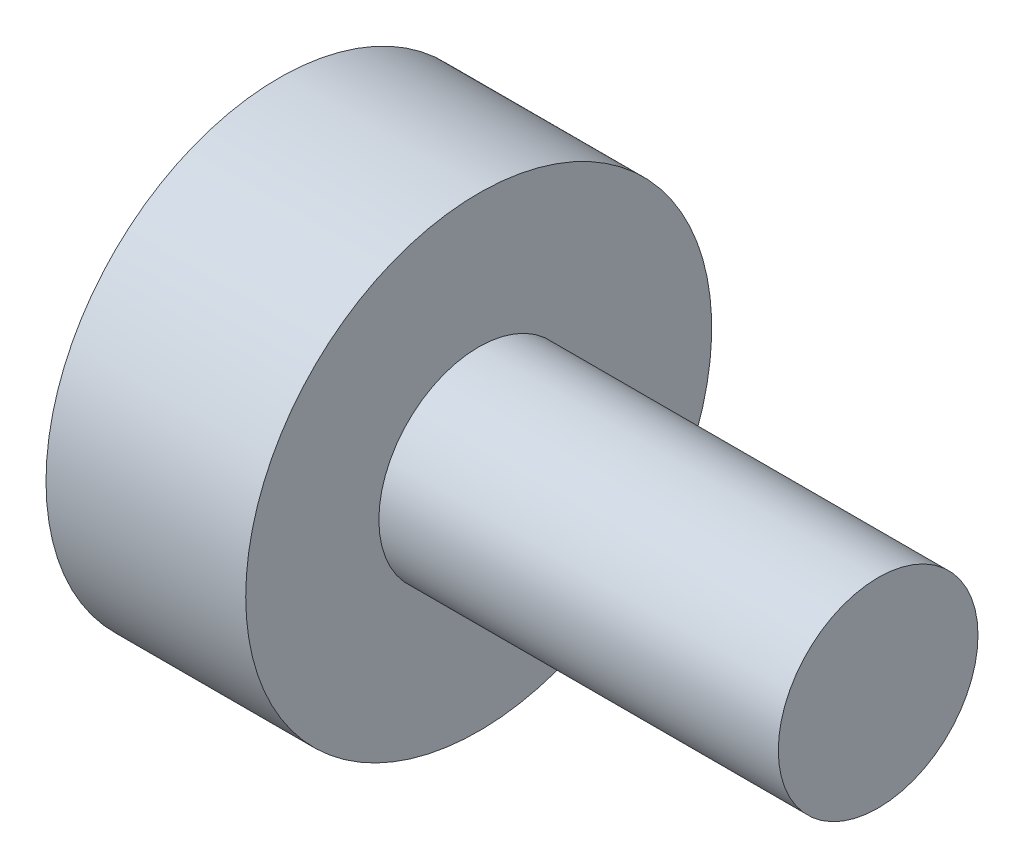
SolidWorks part; units mm, degrees
ref_plane "Спереди" through (0, 0, 0) normal (0, 0, 1) x (1, 0, 0)
ref_plane "Сверху" through (0, 0, 0) normal (0, 1, 0) x (1, 0, 0)
ref_plane "Справа" through (0, 0, 0) normal (1, 0, 0) x (0, 0, -1)
sketch "Эскиз1" plane through (0, 0, 0) normal (0, 0, 1) x (1, 0, 0)
  line L0 (0, 0) -> (100, 0)
  line L1 (0, 0) -> (0, 20)
  line L2 (0, 20) -> (10, 20)
  line L3 (10, 20) -> (10, 35)
  line L4 (10, 35) -> (40, 35)
  line L5 (40, 35) -> (40, 15)
  line L6 (40, 15) -> (100, 15)
  line L7 (100, 0) -> (100, 15)
revolve "Повернуть1" add sketch "Эскиз1" angle 360 about L0
sketch "Эскиз2" plane through (0, 0, 0) normal (0, 0, 1) x (1, 0, 0)
  circle A0 centre (0, 0) radius 5
